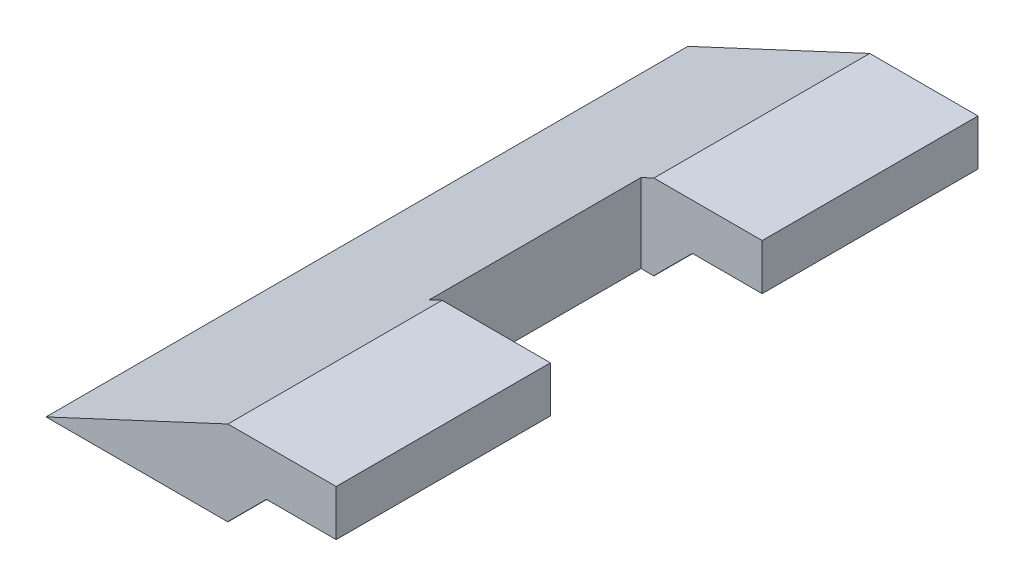
SolidWorks part; units mm, degrees
ref_plane "Спереди" through (0, 0, 0) normal (0, 0, 1) x (1, 0, 0)
ref_plane "Сверху" through (0, 0, 0) normal (0, 1, 0) x (1, 0, 0)
ref_plane "Справа" through (0, 0, 0) normal (1, 0, 0) x (0, 0, -1)
sketch "Эскиз1" plane through (0, 0, 0) normal (0, 0, 1) x (1, 0, 0)
  line L0 (2.867, -4.3036) -> (2.867, -4.2825)
  line L1 (2.867, -4.2825) -> (5.867, -1.2825)
  line L2 (5.867, -1.2825) -> (11.302, -1.2825)
  line L3 (11.302, -1.2825) -> (11.302, 2.3036)
  line L5 (11.302, 2.3036) -> (2.867, 2.3036)
  line L6 (2.867, 2.3036) -> (-11.302, -4.3036)
  line L7 (-11.302, -4.3036) -> (2.867, -4.3036)
extrude "Бобышка-Вытянуть1" add sketch "Эскиз1" along normal blind 50
sketch "Эскиз2" plane through (0, -1.2825, 0) normal (0, -1, 0) x (1, 0, 0)
  line L0 (11.302, 50) -> (11.302, 0) construction
  line L1 (11.302, 16.8131) -> (1.867, 16.8131)
  line L2 (11.302, 16.8131) -> (11.302, 33.3131)
  line L3 (11.302, 33.3131) -> (1.867, 33.3131)
  line L4 (1.867, 16.8131) -> (1.867, 33.3131)
  line L5 (3.898, 17.8131) -> (36.398, 17.8131) construction
  line L6 (36.398, 32.3131) -> (3.898, 32.3131) construction
  line L7 (2.867, 50) -> (2.867, 0) construction
  dimension "D1" = 1
  dimension "D2" = 1
  dimension "D3" = 1
extrude "Вырез-Вытянуть1" cut sketch "Эскиз2" against normal blind 10 and the other way blind 10
